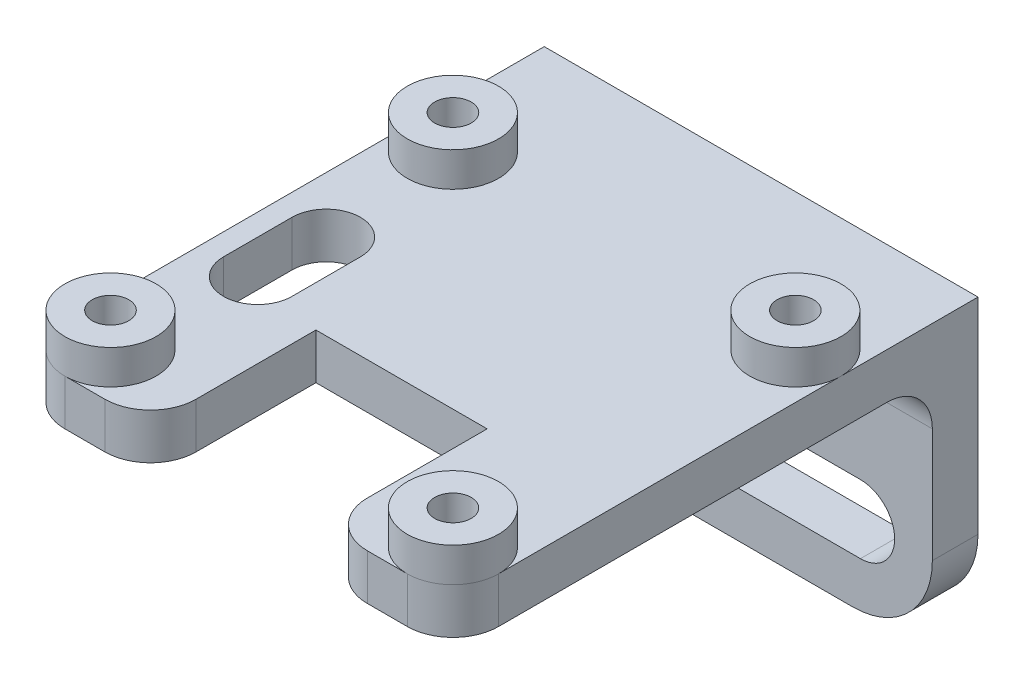
SolidWorks part; units mm, degrees
ref_plane "Front Plane" through (0, 0, 0) normal (0, 0, 1) x (1, 0, 0)
ref_plane "Top Plane" through (0, 0, 0) normal (0, 1, 0) x (1, 0, 0)
ref_plane "Right Plane" through (0, 0, 0) normal (1, 0, 0) x (0, 0, -1)
sketch "Sketch1" plane through (0, 0, 0) normal (0, 0, 1) x (1, 0, 0)
  line L1 (-19, 15) -> (19, 15)
  line L2 (-19, 15) -> (-19, -10)
  line L3 (-19, -10) -> (19, -10)
  line L4 (19, 15) -> (19, -10)
  point P5 (0, -10)
  dimension "D1" = 38
  dimension "D2" = 15
  dimension "D3" = 10
extrude "Boss-Extrude1" add sketch "Sketch1" along normal blind 7
sketch "Sketch2" plane through (0, 0, 7) normal (0, 0, 1) x (1, 0, 0)
  line L0 (19, -10) -> (19, 15) construction
  line L1 (-19, 15) -> (19, 15)
  line L2 (-19, 15) -> (-19, 9)
  line L3 (-19, 9) -> (19, 9)
  line L4 (19, 15) -> (19, 9)
  dimension "D1" = 6
extrude "Boss-Extrude2" add sketch "Sketch2" along normal blind 39
sketch "Sketch3" plane through (0, 0, 7) normal (0, 0, 1) x (1, 0, 0)
  line L3 (-19, 9) -> (19, 9) construction
  line L5 (-12.7, -3) -> (12.7, -3) construction
  line L6 (-12.7, 0) -> (12.7, 0)
  line L7 (-12.7, -6) -> (12.7, -6)
  arc A2 (-12.7, 0) -> (-12.7, -6) centre (-12.7, -3) ccw
  arc A3 (12.7, -6) -> (12.7, 0) centre (12.7, -3) ccw
  point P14 (0, -3)
  dimension "D7" = 3
  dimension "D5" = 12.7
  dimension "D6" = 12.7
  dimension "D8" = 12
extrude "Cut-Extrude2" cut sketch "Sketch3" against normal through all
sketch "Sketch4" plane through (0, 15, 0) normal (0, 1, 0) x (1, 0, 0)
  circle A0 centre (-15, -12) radius 1.6
  dimension "D1" = 3.2
  dimension "D2" = 15
  dimension "D3" = 5
extrude "Cut-Extrude3" cut sketch "Sketch4" against normal through all
sketch "Sketch6" plane through (0, 15, 0) normal (0, 1, 0) x (1, 0, 0)
  circle A0 centre (-15, -12) radius 1.6 construction
  circle A1 centre (-15, -12) radius 1.6
  circle A2 centre (-15, -12) radius 4
  dimension "D1" = 8
extrude "Boss-Extrude3" add sketch "Sketch6" along normal blind 3
pattern_linear "LPattern2" count 2 spacing 30 along (1, 0, 0) count 2 spacing 30 along (0, 0, 1) of "Cut-Extrude3", "Boss-Extrude3"
sketch "Sketch7" plane through (0, 9, 0) normal (0, -1, 0) x (1, 0, 0)
  line L6 (-14.1, 30) -> (-14.1, 24) construction
  line L7 (-11.1, 30) -> (-11.1, 24)
  line L8 (-17.1, 30) -> (-17.1, 24)
  arc A0 (-11.1, 30) -> (-17.1, 30) centre (-14.1, 30) ccw
  arc A1 (-17.1, 24) -> (-11.1, 24) centre (-14.1, 24) ccw
  circle A3 centre (-15, 12) radius 1.6 construction
  point P4 (-14.1, 27)
  dimension "D1" = 3
  dimension "D2" = 14.1
  dimension "D3" = 15
  dimension "D4" = 6
extrude "Cut-Extrude4" cut sketch "Sketch7" against normal through all
sketch "Sketch8" plane through (0, 9, 0) normal (0, -1, 0) x (1, 0, 0)
  line L0 (-19, 46) -> (19, 46) construction
  line L1 (-7.5, 46) -> (7.5, 46)
  line L2 (-7.5, 46) -> (-7.5, 31.5035)
  line L3 (-7.5, 31.5035) -> (7.5, 31.5035)
  line L4 (7.5, 46) -> (7.5, 31.5035)
  point P6 (0, 31.5035)
  dimension "D1" = 15
extrude "Cut-Extrude5" cut sketch "Sketch8" against normal through all
sketch "Sketch10" plane through (0, 9, 0) normal (0, -1, 0) x (1, 0, 0)
  line L8 (7.5, 31.5035) -> (-7.5, 31.5035)
  line L9 (-7.5, 31.5035) -> (-7.5, 46)
  line L10 (-7.5, 46) -> (-19, 46)
  line L11 (-19, 46) -> (-19, 7)
  line L12 (-19, 7) -> (19, 7)
  line L13 (19, 7) -> (19, 46)
  line L14 (19, 46) -> (7.5, 46)
  line L15 (7.5, 46) -> (7.5, 31.5035)
  line L16 (7.5, 31.5035) -> (-7.5, 31.5035)
  line L17 (-7.5, 31.5035) -> (-7.5, 46)
  line L18 (-7.5, 46) -> (-19, 46)
  line L19 (-19, 46) -> (-19, 7)
  line L21 (19, 7) -> (19, 46)
  line L22 (19, 46) -> (7.5, 46)
  line L23 (7.5, 46) -> (7.5, 31.5035)
  line L24 (-19, 7) -> (19, 7)
  dimension "D1" = 0
extrude "Cut-Extrude7" cut sketch "Sketch10" against normal blind 2
sketch "Sketch9" plane through (0, 0, 7) normal (0, 0, 1) x (1, 0, 0)
  line L4 (19, 11) -> (-19, 11)
  line L5 (-19, 11) -> (-19, -10)
  line L6 (-19, -10) -> (19, -10)
  line L7 (19, -10) -> (19, 11)
  line L9 (-19, 11) -> (-19, -10)
  line L10 (-19, -10) -> (19, -10)
  line L11 (19, -10) -> (19, 11)
  line L12 (19, 11) -> (-19, 11)
  dimension "D1" = 0
extrude "Cut-Extrude6" cut sketch "Sketch9" against normal blind 3
fillet "Fillet1" radius 4 1 edges at (0, 11, 4)
fillet "Fillet2" radius 4 4 edges at (-19, 13, 46) (19, 13, 46) (-7.5, 13, 46) (7.5, 13, 46)
fillet "Fillet3" radius 7 2 edges at (-19, -10, 2) (19, -10, 2)
